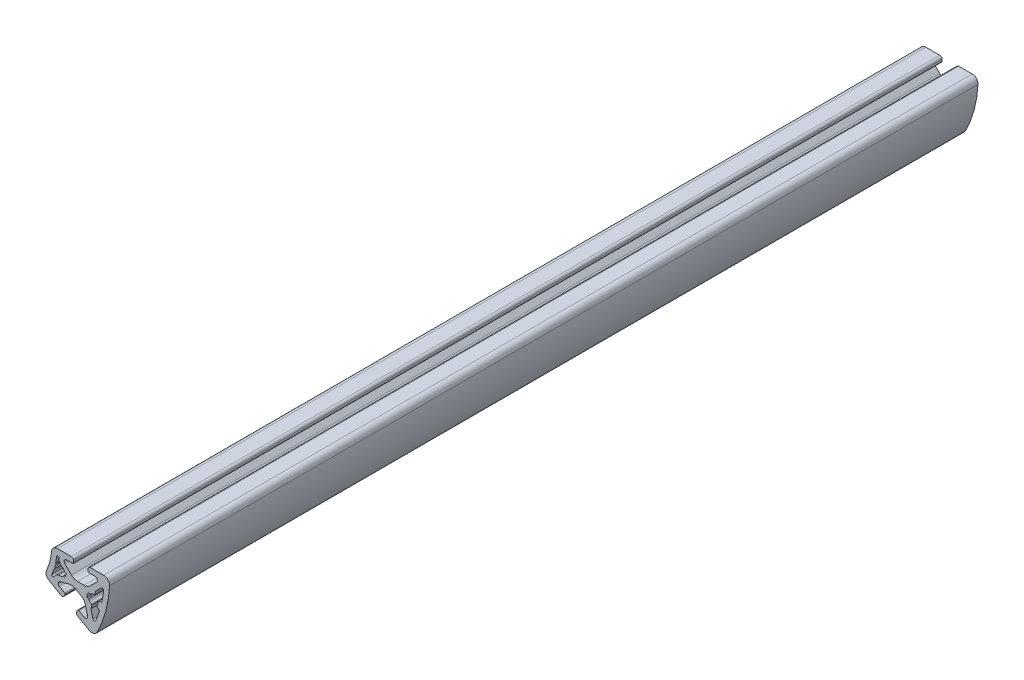
SolidWorks part; units mm, degrees
ref_plane "Plan de face" through (0, 0, 0) normal (0, 0, 1) x (1, 0, 0)
ref_plane "Plan de dessus" through (0, 0, 0) normal (0, 1, 0) x (1, 0, 0)
ref_plane "Plan de droite" through (0, 0, 0) normal (1, 0, 0) x (0, 0, -1)
sketch "Esquisse1" plane through (0, 0, 0) normal (0, 0, 1) x (1, 0, 0)
  line L54 (-2.2778, 7.7646) -> (-7.0689, 7.7646)
  line L55 (-1.4778, 6.2646) -> (-1.4778, 6.9646)
  line L56 (-3.8954, 5.9646) -> (-1.7778, 5.9646)
  line L57 (-2.2337, 2.2933) -> (-4.484, 4.5436)
  line L58 (2.1568, 1.4146) -> (-0.1123, 1.4146)
  line L59 (6.5284, 4.5436) -> (4.2781, 2.2933)
  line L60 (3.8222, 5.9646) -> (5.9398, 5.9646)
  line L61 (3.5222, 6.9646) -> (3.5222, 6.2646)
  line L62 (8.9696, 7.7646) -> (4.3222, 7.7646)
  line L63 (-0.1611, -8.8728) -> (3.8856, -11.2091)
  line L64 (-0.0827, -7.1864) -> (-0.4327, -7.7926)
  line L65 (2.161, -8.1354) -> (0.3271, -7.0766)
  line L66 (2.5576, -4.1251) -> (3.3812, -7.199)
  line L67 (-0.8053, -1.1689) -> (1.1598, -2.3035)
  line L68 (-6.1558, -1.6929) -> (-3.0818, -0.8692)
  line L69 (-4.5227, -4.2766) -> (-6.3565, -3.2178)
  line L70 (-4.7628, -5.2926) -> (-4.4128, -4.6864)
  line L71 (-10.0041, -3.1899) -> (-5.8341, -5.5974)
  line L72 (-7.324, 5.241) -> (-7.6616, 3.1962)
  line L73 (-4.2803, 2.0022) -> (-4.5769, 2.0817)
  line L74 (-5.0039, 0.4879) -> (-4.7074, 0.4085)
  line L75 (-8.2326, 1.0651) -> (-8.9626, -0.8745)
  line L76 (-8.0545, 1.2074) -> (-8.094, 1.1968)
  line L77 (-7.6074, 3.0128) -> (-7.5785, 2.9839)
  line L102 (4.039, -0.2269) -> (3.7424, -0.1474)
  line L103 (6.1065, 1.5388) -> (5.7891, 0.3541)
  line L104 (8.0928, 3.563) -> (6.1583, 1.6285)
  line L105 (8.3164, -0.5063) -> (8.9427, 3.149)
  line L106 (7.0896, -0.9464) -> (8.1729, -0.6561)
  line L107 (7.4066, -3.5159) -> (6.6136, -2.7229)
  line L108 (6.1707, -7.1962) -> (7.4559, -3.7175)
  line L109 (4.5196, -4.4871) -> (5.2277, -7.1298)
  line L110 (4.8371, -3.1989) -> (4.5196, -4.3836)
  line L111 (3.3154, -1.7412) -> (3.612, -1.8207)
  arc A66 (-1.4778, 6.9646) -> (-2.2778, 7.7646) centre (-2.2778, 6.9646) ccw
  arc A67 (-1.7778, 5.9646) -> (-1.4778, 6.2646) centre (-1.7778, 6.2646) ccw
  arc A68 (-3.8954, 5.9646) -> (-4.484, 4.5436) centre (-3.8954, 5.1322) ccw
  arc A69 (-2.2337, 2.2933) -> (-0.1123, 1.4146) centre (-0.1123, 4.4146) ccw
  arc A70 (2.1568, 1.4146) -> (4.2781, 2.2933) centre (2.1568, 4.4146) ccw
  arc A71 (6.5284, 4.5436) -> (5.9398, 5.9646) centre (5.9398, 5.1322) ccw
  arc A72 (3.5222, 6.2646) -> (3.8222, 5.9646) centre (3.8222, 6.2646) ccw
  arc A73 (4.3222, 7.7646) -> (3.5222, 6.9646) centre (4.3222, 6.9646) ccw
  arc A74 (10.9668, 5.6593) -> (8.9696, 7.7646) centre (8.9696, 5.7646) ccw
  arc A75 (6.6679, -10.3845) -> (10.9668, 5.6593) centre (-28.9778, 7.7646) ccw
  arc A76 (3.8856, -11.2091) -> (6.6679, -10.3845) centre (4.8856, -9.477) ccw
  arc A77 (-0.4327, -7.7926) -> (-0.1611, -8.8728) centre (0.2601, -8.1926) ccw
  arc A78 (0.3271, -7.0766) -> (-0.0827, -7.1864) centre (0.1771, -7.3364) ccw
  arc A79 (2.161, -8.1354) -> (3.3812, -7.199) centre (2.5772, -7.4145) ccw
  arc A80 (2.5576, -4.1251) -> (1.1598, -2.3035) centre (-0.3402, -4.9015) ccw
  arc A81 (-0.8053, -1.1689) -> (-3.0818, -0.8692) centre (-2.3053, -3.767) ccw
  arc A82 (-6.1558, -1.6929) -> (-6.3565, -3.2178) centre (-5.9403, -2.4969) ccw
  arc A83 (-4.4128, -4.6864) -> (-4.5227, -4.2766) centre (-4.6727, -4.5364) ccw
  arc A84 (-5.8341, -5.5974) -> (-4.7628, -5.2926) centre (-5.4557, -4.8926) ccw
  arc A85 (-10.8199, -0.6194) -> (-10.0041, -3.1899) centre (-9.0041, -1.4578) ccw
  arc A86 (-10.8199, -0.6194) -> (-9.0606, 5.9464) centre (-28.9778, 7.7646) ccw
  arc A87 (-7.0689, 7.7646) -> (-9.0606, 5.9464) centre (-7.0689, 5.7646) ccw
  arc A120 (-6.5267, 5.1866) -> (-7.324, 5.241) centre (-6.9267, 5.1947) ccw
  arc A121 (-6.5267, 5.1866) -> (-5.7513, 3.2669) centre (-3.8949, 5.1333) ccw
  arc A122 (-5.7513, 3.2669) -> (-5.6824, 3.2222) centre (-5.6102, 3.4087) ccw
  arc A123 (-4.7146, 2.2109) -> (-5.6824, 3.2222) centre (-6.278, 1.6834) ccw
  arc A124 (-4.7146, 2.2109) -> (-4.5769, 2.0817) centre (-4.5251, 2.2749) ccw
  arc A125 (-4.1325, 1.8219) -> (-4.2803, 2.0022) centre (-4.3321, 1.8091) ccw
  arc A126 (-4.4892, 0.4907) -> (-4.1325, 1.8219) centre (-6.278, 1.6834) ccw
  arc A127 (-4.7074, 0.4085) -> (-4.4892, 0.4907) centre (-4.6556, 0.6016) ccw
  arc A128 (-5.0039, 0.4879) -> (-5.1878, 0.4449) centre (-5.0557, 0.2947) ccw
  arc A129 (-6.5316, 0.053) -> (-5.1878, 0.4449) centre (-6.278, 1.6834) ccw
  arc A130 (-6.5316, 0.053) -> (-6.6136, 0.0487) centre (-6.5623, -0.1446) ccw
  arc A131 (-6.6136, 0.0487) -> (-8.245, -1.226) centre (-5.9391, -2.4958) ccw
  arc A132 (-8.9626, -0.8745) -> (-8.245, -1.226) centre (-8.5954, -1.0331) ccw
  arc A133 (-8.094, 1.1968) -> (-8.2326, 1.0651) centre (-8.0423, 1.0036) ccw
  arc A134 (-8.0545, 1.2074) -> (-7.9086, 1.4312) centre (-8.1063, 1.4006) ccw
  arc A135 (-7.564, 2.7172) -> (-7.9086, 1.4312) centre (-6.278, 1.6834) ccw
  arc A136 (-7.564, 2.7172) -> (-7.5785, 2.9839) centre (-7.7199, 2.8425) ccw
  arc A137 (-7.6616, 3.1962) -> (-7.6074, 3.0128) centre (-7.466, 3.1542) ccw
  arc A174 (3.5243, -0.2297) -> (3.1676, -1.5609) centre (5.3131, -1.4224) ccw
  arc A175 (3.7424, -0.1474) -> (3.5243, -0.2297) centre (3.6907, -0.3406) ccw
  arc A176 (4.039, -0.2269) -> (4.2229, -0.1839) centre (4.0908, -0.0337) ccw
  arc A177 (5.5653, 0.2082) -> (4.2229, -0.1839) centre (5.3131, -1.4224) ccw
  arc A178 (5.5653, 0.2082) -> (5.7891, 0.3541) centre (5.5959, 0.4058) ccw
  arc A179 (6.1583, 1.6285) -> (6.1065, 1.5388) centre (6.2997, 1.487) ccw
  arc A180 (8.9427, 3.149) -> (8.0928, 3.563) centre (8.4464, 3.2094) ccw
  arc A181 (8.1729, -0.6561) -> (8.3164, -0.5063) centre (8.1211, -0.4629) ccw
  arc A182 (7.0896, -0.9464) -> (6.9437, -1.1702) centre (7.1413, -1.1396) ccw
  arc A183 (6.5991, -2.4562) -> (6.9437, -1.1702) centre (5.3131, -1.4224) ccw
  arc A184 (6.5991, -2.4562) -> (6.6136, -2.7229) centre (6.755, -2.5815) ccw
  arc A185 (7.4559, -3.7175) -> (7.4066, -3.5159) centre (7.2652, -3.6573) ccw
  arc A186 (5.2277, -7.1298) -> (6.1707, -7.1962) centre (5.7107, -7.0004) ccw
  arc A187 (4.5196, -4.3836) -> (4.5196, -4.4871) centre (4.7128, -4.4354) ccw
  arc A188 (4.8371, -3.1989) -> (4.7162, -2.9607) centre (4.6439, -3.1471) ccw
  arc A189 (3.7497, -1.9499) -> (4.7162, -2.9607) centre (5.3131, -1.4224) ccw
  arc A190 (3.7497, -1.9499) -> (3.612, -1.8207) centre (3.5602, -2.0139) ccw
  arc A191 (3.1676, -1.5609) -> (3.3154, -1.7412) centre (3.3671, -1.548) ccw
extrude "Boss.-Extru.1" add sketch "Esquisse1" along normal blind 300
